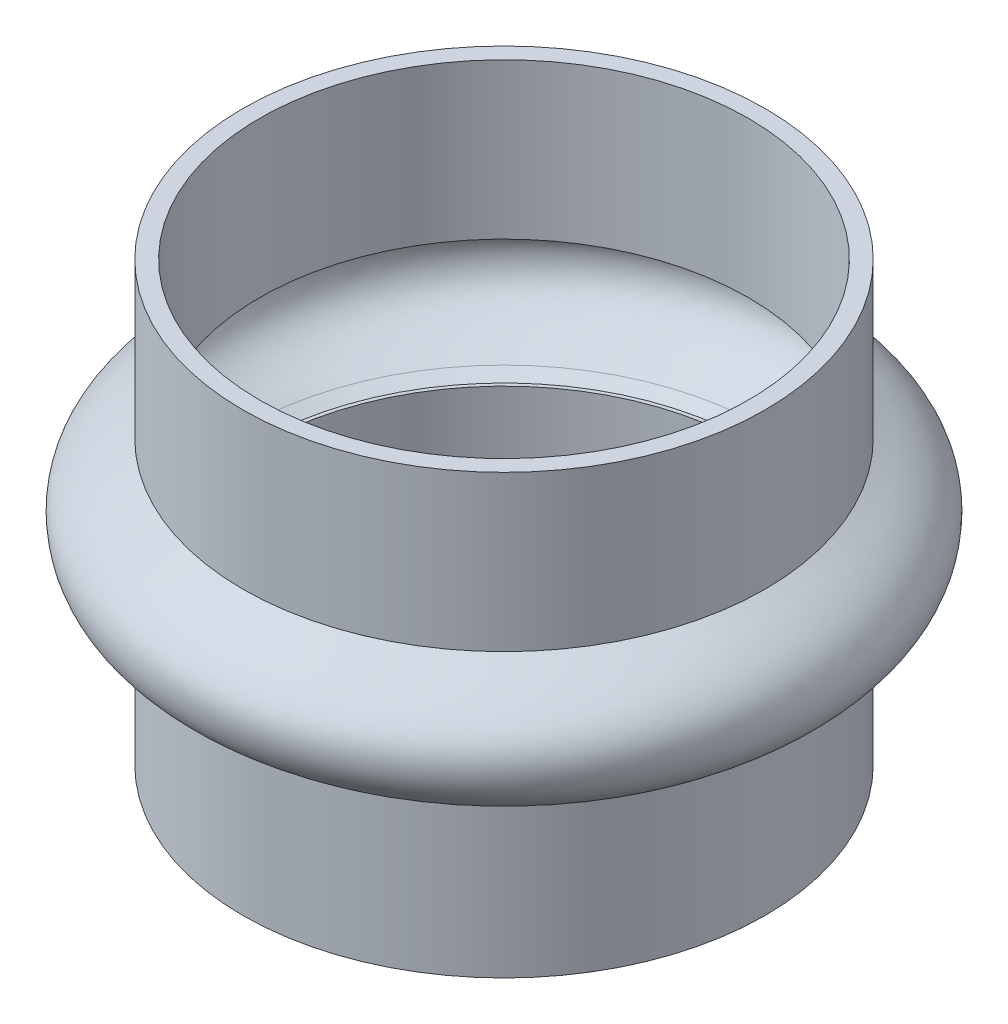
SolidWorks part; units mm, degrees
ref_plane "Front Plane" through (0, 0, 0) normal (0, 0, 1) x (1, 0, 0)
ref_plane "Top Plane" through (0, 0, 0) normal (0, 1, 0) x (1, 0, 0)
ref_plane "Right Plane" through (0, 0, 0) normal (1, 0, 0) x (0, 0, -1)
sketch "Sketch1" plane through (0, 0, 0) normal (0, 0, 1) x (1, 0, 0)
  line L0 (-921.4581, 1439.0368) -> (211.8752, 1439.0368) construction
  line L1 (-99.3333, 446.5) -> (103.3333, 446.5) construction
  line L2 (3.2388, 58.9758) -> (39.625, 58.9758) construction
  line L3 (24.1403, 76.5393) -> (24.1403, 40.3207) construction
  line L4 (7.3253, 63.4119) -> (24.1403, 63.4119) construction
  line L5 (7.3253, 63.4119) -> (24.1403, 76.5393) construction
  line L6 (7.3253, 63.4119) -> (8.411, 63.4119)
  line L7 (8.411, 63.4119) -> (7.5555, 62.9681)
  line L8 (7.3735, 55.6488) -> (8.166, 55.2112)
  line L9 (8.166, 55.2112) -> (7.1318, 55.2112)
  spline S0 degree 3 poles (7.3253, 63.4119) (6.0111, 62.7301) (2.9718, 61.4252) (3.4634, 56.9126) (5.9426, 55.8679) (7.1318, 55.2112) knots 0 0 0 0 0.43 0.624673 1 1 1 1
  spline S1 degree 1 poles (7.5555, 62.9681) (7.3735, 55.6488) knots 0 0 1 1 construction
  spline S2 degree 3 poles (7.5555, 62.9681) (7.35, 62.8614) (6.9471, 62.6604) (6.0541, 62.2018) (4.9545, 61.5406) (4.1595, 60.7257) (3.8436, 60.0138) (3.7346, 59.1782) (3.99, 58.0647) (4.8318, 57.1066) (6.086, 56.3114) (6.9493, 55.8831) (7.3735, 55.6488) knots 0 0 0 0 0.0625 0.125 0.25 0.375 0.4375 0.5 0.625 0.75 0.875 1 1 1 1
  dimension "D1" = 36.3862
  dimension "D2" = 0.5
  dimension "D3" = 16.815
revolve "Revolve1" add sketch "Sketch1" angle 360 about L3
ref_plane "Plane1" through (0, 59.3115, 0) normal (0, 1, 0) x (1, 0, 0)
sketch "Sketch2" plane through (0, 63.4119, 0) normal (0, 1, 0) x (1, 0, 0)
  circle A0 centre (24.1403, 0) radius 16.815
  circle A1 centre (24.1403, 0) radius 16.815 construction
  circle A2 centre (24.1403, 0) radius 15.7293
  circle A3 centre (24.1403, 0) radius 15.7293 construction
extrude "Boss-Extrude1" add sketch "Sketch2" along normal blind 10
mirror "Mirror1" about plane through (0, 59.3115, 0) normal (0, 1, 0) of "Boss-Extrude1"
